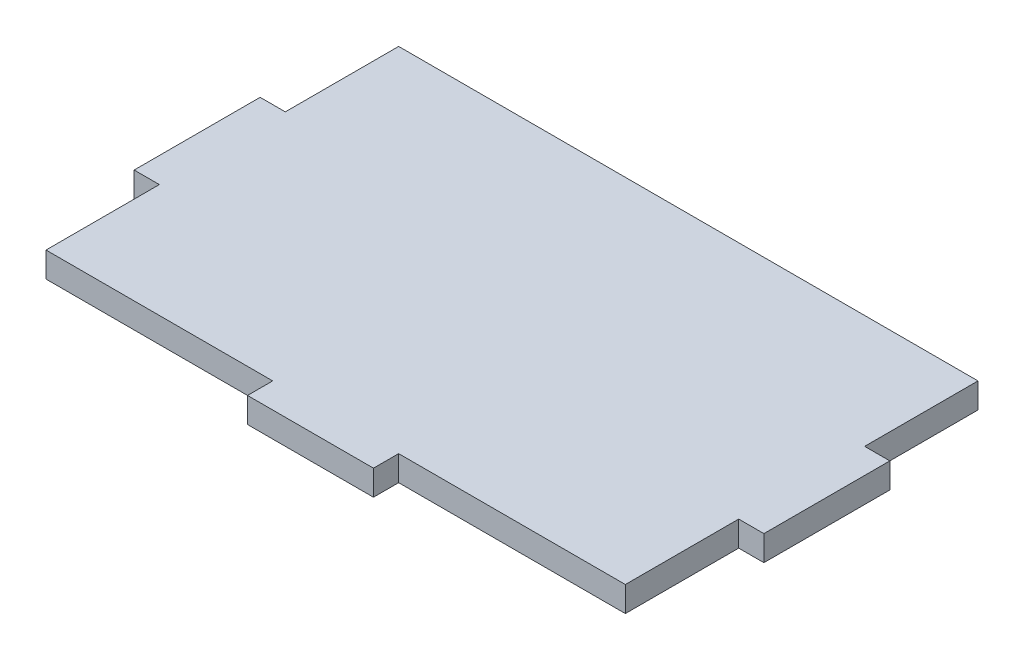
SolidWorks part; units mm, degrees
ref_plane "前视基准面" through (0, 0, 0) normal (0, 0, 1) x (1, 0, 0)
ref_plane "上视基准面" through (0, 0, 0) normal (0, 1, 0) x (1, 0, 0)
ref_plane "右视基准面" through (0, 0, 0) normal (1, 0, 0) x (0, 0, -1)
sketch "草图1" plane through (0, 0, 0) normal (0, 1, 0) x (1, 0, 0)
  line L0 (0, 56) -> (92, 56)
  line L1 (0, 0) -> (92, 0)
  line L2 (0, 0) -> (0, 56)
  line L4 (92, 0) -> (92, 56)
  line L5 (0, 38) -> (-4, 38)
  line L6 (0, 38) -> (0, 18)
  line L7 (0, 18) -> (-4, 18)
  line L8 (-4, 38) -> (-4, 18)
  line L9 (92, 38) -> (96, 38)
  line L10 (92, 38) -> (92, 18)
  line L11 (92, 18) -> (96, 18)
  line L12 (96, 38) -> (96, 18)
  line L45 (56, 0) -> (36, 0)
  line L46 (56, 0) -> (56, -4)
  line L47 (56, -4) -> (36, -4)
  line L48 (36, 0) -> (36, -4)
  point P5 (92, 28)
  point P6 (0, 28)
  point P7 (92, 38)
  point P8 (92, 20)
  point P9 (0, 38)
  point P10 (0, 20)
  point P68 (56, 0)
  point P69 (40, 0)
  point P70 (46, 0)
extrude "凸台-拉伸2" add sketch "草图1" along normal blind 4
